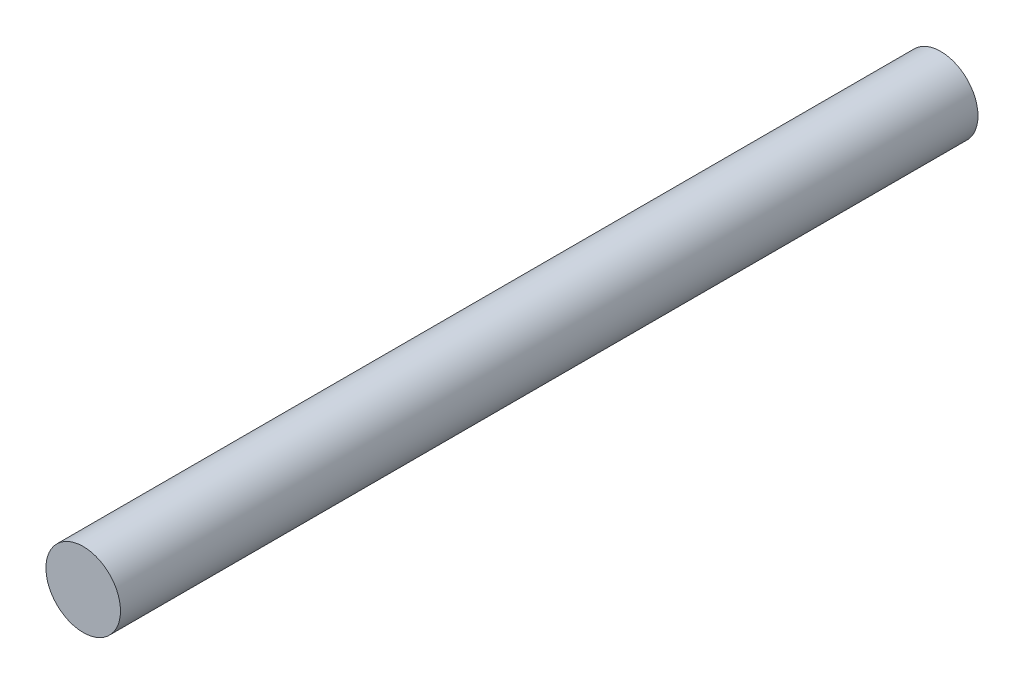
SolidWorks part; units mm, degrees
ref_plane "Front Plane" through (0, 0, 0) normal (0, 0, 1) x (1, 0, 0)
ref_plane "Top Plane" through (0, 0, 0) normal (0, 1, 0) x (1, 0, 0)
ref_plane "Right Plane" through (0, 0, 0) normal (1, 0, 0) x (0, 0, -1)
sketch "Sketch1" plane through (0, 0, 0) normal (0, 0, 1) x (1, 0, 0)
  circle A0 centre (0, 0) radius 12.7
  dimension "D1" = 25.4
extrude "Boss-Extrude1" add sketch "Sketch1" along normal blind 292.1 contours A0
